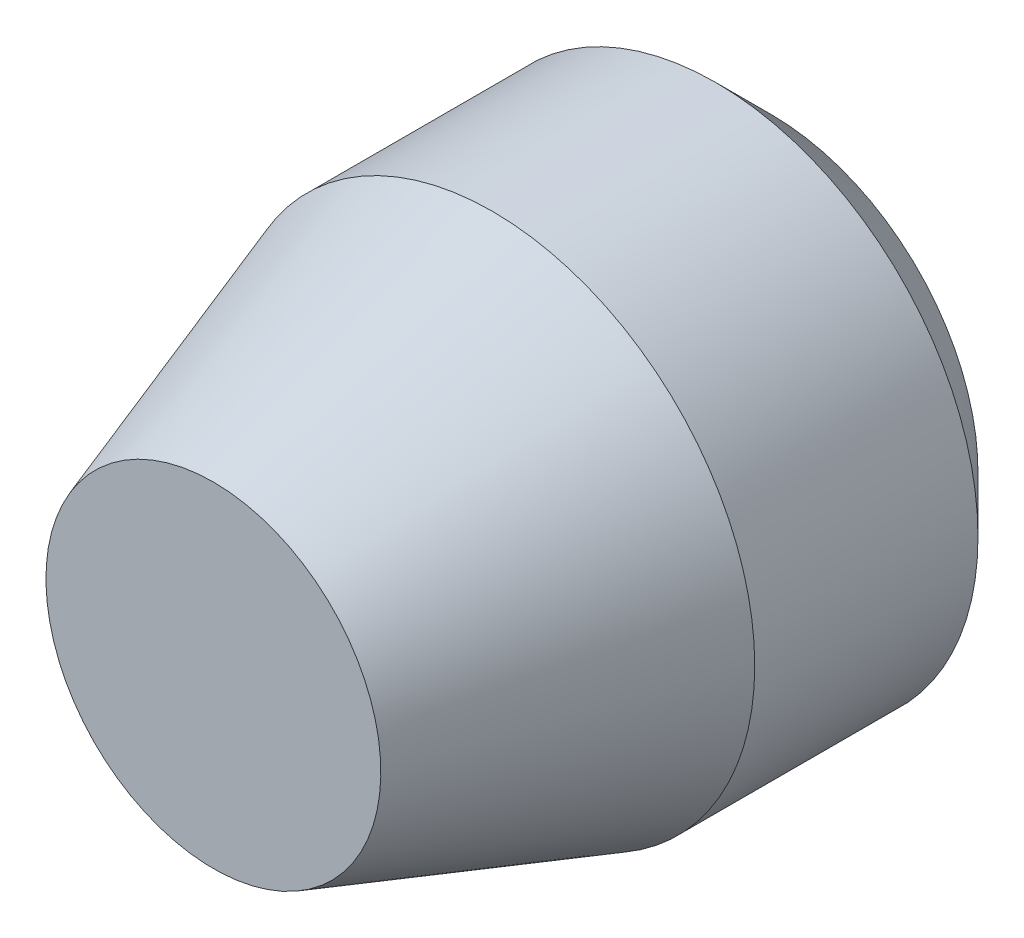
SolidWorks part; units mm, degrees
ref_plane "Plano frontal" through (0, 0, 0) normal (0, 0, 1) x (1, 0, 0)
ref_plane "Plano superior" through (0, 0, 0) normal (0, 1, 0) x (1, 0, 0)
ref_plane "Plano direito" through (0, 0, 0) normal (1, 0, 0) x (0, 0, -1)
sketch "Esboço3" plane through (0, 0, 0) normal (1, 0, 0) x (0, 0, -1)
  line L0 (0, 0) -> (0, 3)
  line L1 (0, 3) -> (5, 4.7)
  line L2 (5, 4.7) -> (10, 4.7)
  line L3 (10, 4.7) -> (10, 0)
  line L4 (10, 0) -> (0, 0)
  dimension "D1" = 3
  dimension "D2" = 4.7
  dimension "D3" = 5
  dimension "D4" = 10
revolve "Revolução1" add sketch "Esboço3" angle 360 about L4
chamfer "Chanfro1" distance 1 angle 45 1 edges at (0, 4.7, -10)
